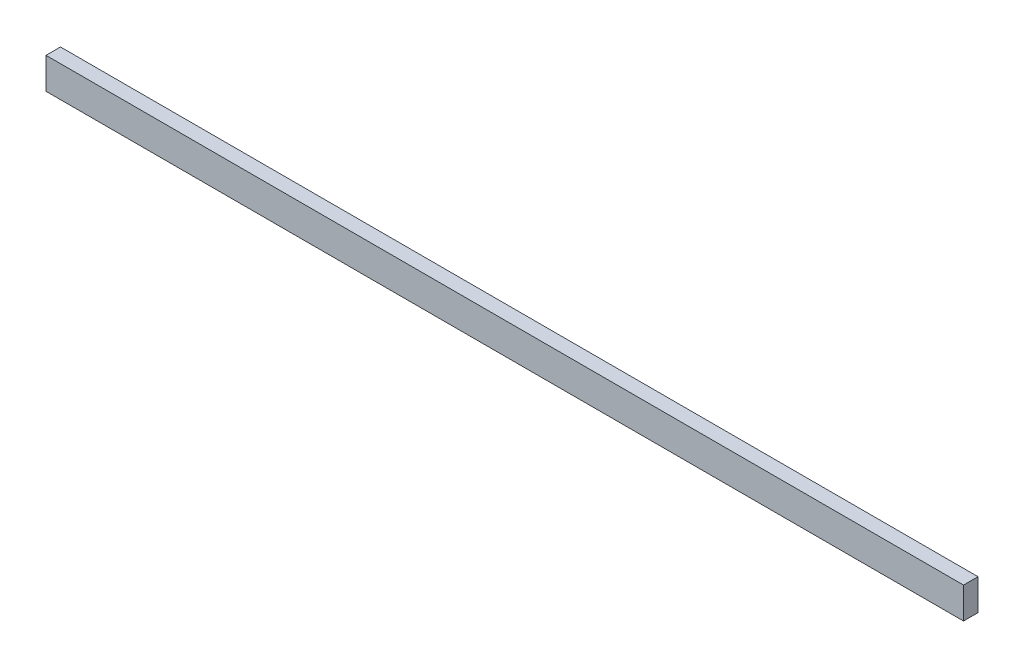
SolidWorks part; units mm, degrees
ref_plane "Front Plane" through (0, 0, 0) normal (0, 0, 1) x (1, 0, 0)
ref_plane "Top Plane" through (0, 0, 0) normal (0, 1, 0) x (1, 0, 0)
ref_plane "Right Plane" through (0, 0, 0) normal (1, 0, 0) x (0, 0, -1)
sketch "Sketch1" plane through (0, 0, 0) normal (0, 1, 0) x (1, 0, 0)
  line L1 (-120.65, -1.905) -> (120.65, -1.905)
  line L2 (-120.65, -1.905) -> (-120.65, 1.905)
  line L3 (-120.65, 1.905) -> (120.65, 1.905)
  line L4 (120.65, -1.905) -> (120.65, 1.905)
  line L5 (-120.65, -1.905) -> (120.65, 1.905) construction
  line L6 (-120.65, 1.905) -> (120.65, -1.905) construction
  point P0 (0, 0)
  dimension "D1" = 3.81
  dimension "D2" = 241.3
extrude "Boss-Extrude1" add sketch "Sketch1" along normal blind 8.2
